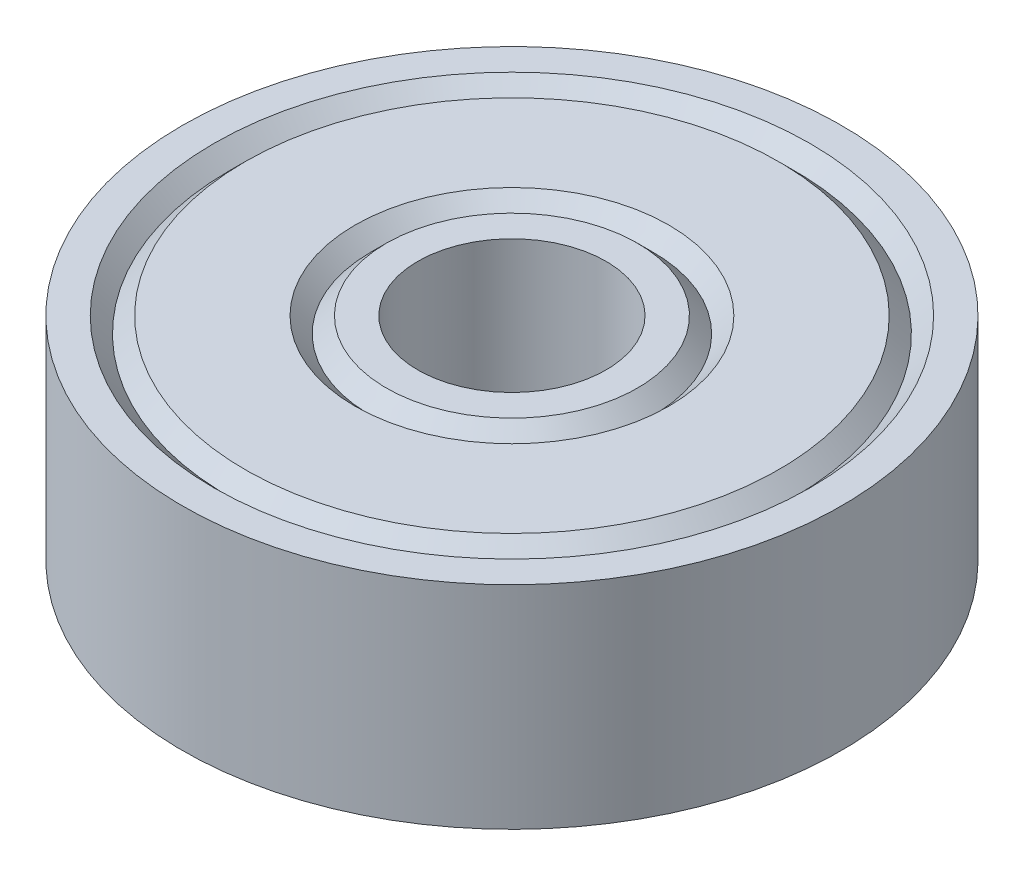
SolidWorks part; units mm, degrees
ref_plane "Front Plane" through (0, 0, 0) normal (0, 0, 1) x (1, 0, 0)
ref_plane "Top Plane" through (0, 0, 0) normal (0, 1, 0) x (1, 0, 0)
ref_plane "Right Plane" through (0, 0, 0) normal (1, 0, 0) x (0, 0, -1)
sketch "Sketch1" plane through (0, 0, 0) normal (0, 0, 1) x (1, 0, 0)
  line L0 (0, 4.5) -> (0, -4.5) construction
  line L1 (-4, 4.5) -> (-5.3333, 4.5)
  line L2 (-4, 4.5) -> (-4, -4.5)
  line L3 (-4, -4.5) -> (-5.3333, -4.5)
  line L4 (-14, 4.5) -> (-14, -4.5)
  line L5 (-12.6667, 4.5) -> (-12, 3.8333)
  line L6 (-12, 3.8333) -> (-11.3333, 4.5)
  line L7 (-6.6667, 4.5) -> (-6, 3.8333)
  line L8 (-6, 3.8333) -> (-5.3333, 4.5)
  line L9 (-12.6667, -4.5) -> (-12, -3.8333)
  line L10 (-12, -3.8333) -> (-11.3333, -4.5)
  line L11 (-6.6667, -4.5) -> (-6, -3.8333)
  line L12 (-6, -3.8333) -> (-5.3333, -4.5)
  line L13 (-6.6667, -4.5) -> (-11.3333, -4.5)
  line L14 (-12.6667, -4.5) -> (-14, -4.5)
  line L15 (-12.6667, 4.5) -> (-14, 4.5)
  line L16 (-6.6667, 4.5) -> (-11.3333, 4.5)
  line L17 (-12, 3.8333) -> (-6, 3.8333) construction
  line L18 (-12, 3.8333) -> (-12, -3.8333) construction
  line L19 (-6, -3.8333) -> (-12, -3.8333) construction
  line L20 (-6, 3.8333) -> (-6, -3.8333) construction
  line L21 (-12, 0) -> (-10, 0) construction
  line L22 (-5.3333, 4.5) -> (-6.6667, 4.5) construction
  line L23 (-10, 0) -> (-8, 0) construction
  line L24 (-12, 0) -> (-14, 0) construction
  line L25 (-8, 0) -> (-6, 0) construction
  line L26 (-6, 0) -> (-4, 0) construction
  dimension "D1" = 9
  dimension "D2" = 8
  dimension "D3" = 28
revolve "Revolve1" add sketch "Sketch1" angle 360 about L0
